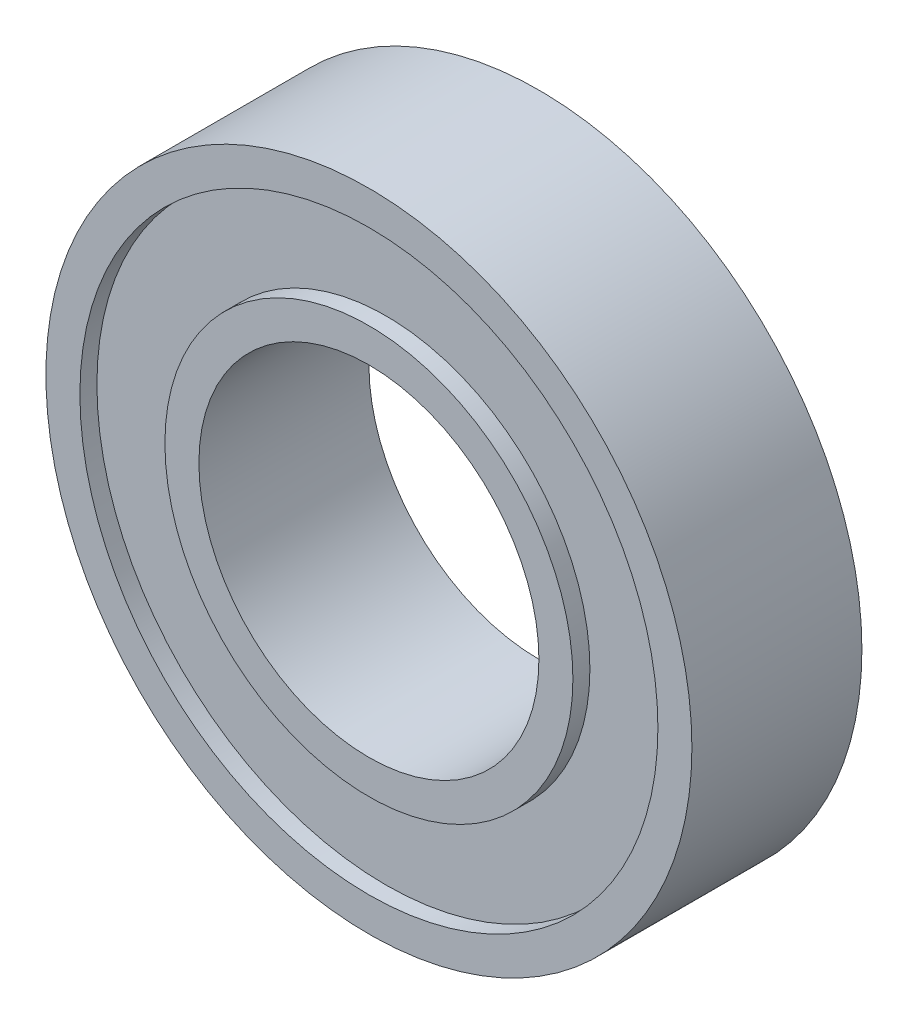
SolidWorks part; units mm, degrees
material "Plain Carbon Steel"
ref_plane "Front Plane" through (0, 0, 0) normal (0, 0, 1) x (1, 0, 0)
ref_plane "Top Plane" through (0, 0, 0) normal (0, 1, 0) x (1, 0, 0)
ref_plane "Right Plane" through (0, 0, 0) normal (1, 0, 0) x (0, 0, -1)
sketch "Sketch1" plane through (0, 0, 0) normal (1, 0, 0) x (0, 0, -1)
  line L0 (-2.5, 6) -> (-2.5, 5)
  line L1 (-2.5, 9.5) -> (2.5, 9.5)
  line L2 (-2.5, 9.5) -> (-2.5, 8.5)
  line L3 (-2.5, 5) -> (2.5, 5)
  line L4 (2.5, 9.5) -> (2.5, 8.5)
  line L5 (-2.5, 8.5) -> (-2, 8.5)
  line L7 (-2.5, 6) -> (-2, 6)
  line L8 (-2, 8.5) -> (-2, 6)
  line L9 (2.5, 8.5) -> (2, 8.5)
  line L11 (2.5, 6) -> (2, 6)
  line L12 (2, 8.5) -> (2, 6)
  line L13 (2.5, 6) -> (2.5, 5)
  line L14 (0, 0) -> (2.7954, 0) construction
  point P15 (0, 5)
  dimension "D1" = 5
  dimension "D2" = 10
  dimension "D3" = 19
  dimension "D4" = 1
  dimension "D5" = 4
revolve "Revolve1" add sketch "Sketch1" angle 360 about L14
